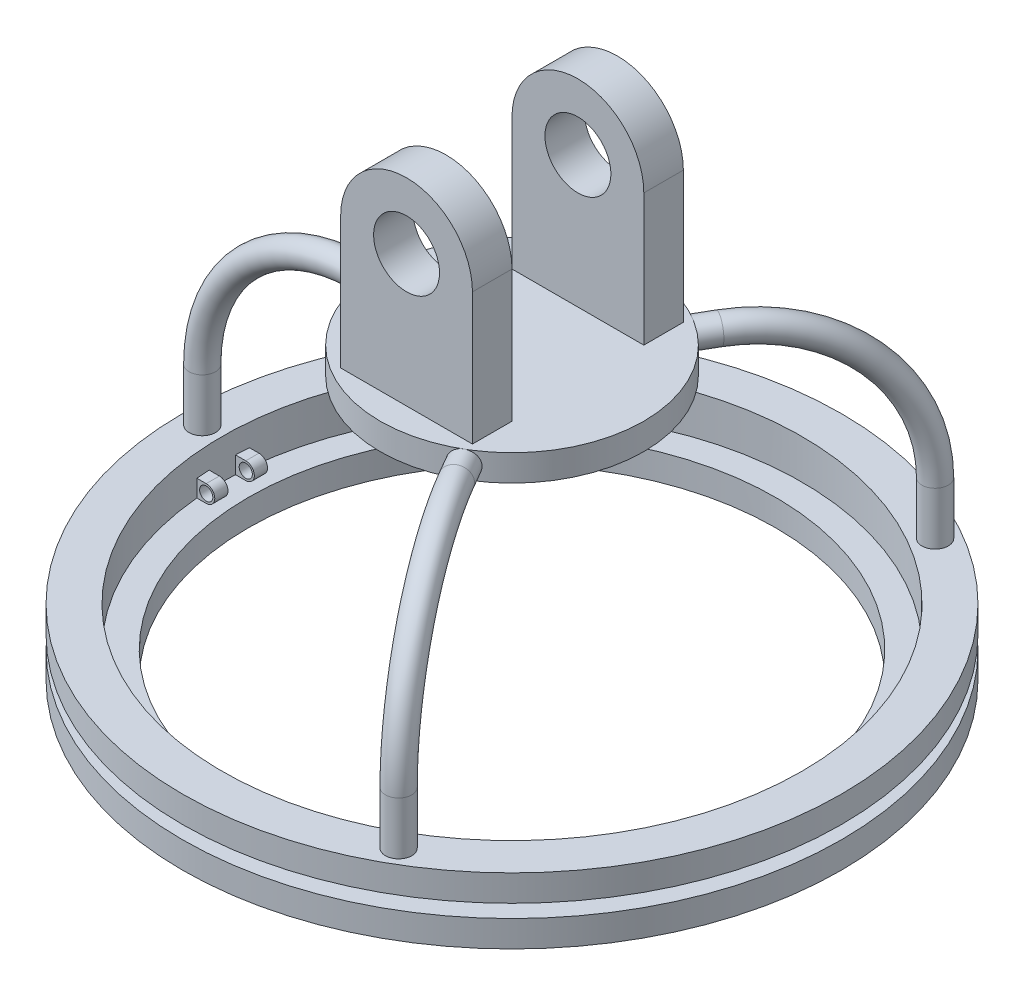
SolidWorks part; units mm, degrees
material "Alumina"
ref_plane "Front Plane" through (0, 0, 0) normal (0, 0, 1) x (1, 0, 0)
ref_plane "Top Plane" through (0, 0, 0) normal (0, 1, 0) x (1, 0, 0)
ref_plane "Right Plane" through (0, 0, 0) normal (1, 0, 0) x (0, 0, -1)
sketch "Sketch1" plane through (0, 0, 0) normal (0, 0, 1) x (1, 0, 0)
  line L0 (0, -571.377) -> (0, 27997.4744) construction
  line L3 (31.75, 6.35) -> (31.75, 3.81)
  line L4 (31.75, 3.81) -> (29.21, 3.81)
  line L5 (29.21, 3.81) -> (29.21, 2.54)
  line L6 (29.21, 2.54) -> (31.75, 2.54)
  line L7 (31.75, 2.54) -> (31.75, 0)
  line L8 (31.75, 0) -> (0, 0)
  line L9 (27.94, 6.35) -> (31.75, 6.35)
  line L10 (27.94, 6.35) -> (27.94, 2.54)
  line L11 (27.94, 2.54) -> (0, 2.54)
  line L12 (0, 2.54) -> (0, 0)
  dimension "D1" = 31.75
  dimension "D3" = 2.54
  dimension "D4" = 2.54
  dimension "D5" = 1.27
  dimension "D6" = 1.27
  dimension "D7" = 2.54
revolve "Revolve1" add sketch "Sketch1" angle 360 about L0
ref_plane "Plane1" through (0, 25.4, 0) normal (0, 1, 0) x (1, 0, 0)
sketch "Sketch2" plane through (0, 2.54, 0) normal (0, 1, 0) x (1, 0, 0)
  circle A0 centre (0, 0) radius 25.4
  dimension "D1" = 50.8
extrude "Cut-Extrude1" cut sketch "Sketch2" against normal up to surface (2.54 mm away) up to face at (31.75, 0, 0)
sketch "Sketch3" plane through (0, 25.4, 0) normal (0, 1, 0) x (1, 0, 0)
  circle A0 centre (0, 0) radius 12.7
  dimension "D1" = 25.4
extrude "Boss-Extrude1" add sketch "Sketch3" along normal blind 2.54 separate body
sketch "Sketch5" plane through (0, 27.94, 0) normal (0, 1, 0) x (1, 0, 0)
  line L0 (-6.35, 10.16) -> (6.35, 10.16)
  line L1 (6.35, 10.16) -> (6.35, 6.35)
  line L2 (6.35, 6.35) -> (-6.35, 6.35)
  line L3 (-6.35, 6.35) -> (-6.35, 10.16)
  line L4 (0, 6.35) -> (0, 0) construction
  dimension "D1" = 6.35
  dimension "D2" = 3.81
  dimension "D3" = 12.7
extrude "Boss-Extrude2" add sketch "Sketch5" along normal blind 12.7
sketch "Sketch6" plane through (0, 0, -6.35) normal (0, 0, 1) x (1, 0, 0)
  line L0 (-6.35, 40.64) -> (6.35, 40.64)
  arc A0 (6.35, 40.64) -> (-6.35, 40.64) centre (0, 40.64) ccw
extrude "Boss-Extrude3" add sketch "Sketch6" against normal up to surface (3.81 mm away) up to face at (0, 34.29, -10.16)
mirror "Mirror1" about plane through (0, 0, 0) normal (0, 0, 1) of "Boss-Extrude3", "Boss-Extrude2"
sketch "Sketch10" plane through (0, 0, -10.16) normal (0, 0, -1) x (-1, 0, 0)
  line L0 (0, 46.99) -> (0, 40.64) construction
  circle A0 centre (0, 40.64) radius 3.175
  arc A1 (6.35, 40.64) -> (-6.35, 40.64) centre (0, 40.64) ccw construction
  dimension "D2" = 6.35
  dimension "D1" = 6.35
extrude "Cut-Extrude2" cut sketch "Sketch10" against normal up to surface (20.32 mm away) up to face at (0, 35.8775, 10.16)
sketch "Sketch11" plane through (0, 0, 0) normal (0, 1, 0) x (1, 0, 0)
  line L0 (-1000, 0) -> (49000, 0) construction
  line L1 (0, 0) -> (-25000, 43301.2702) construction
  line L2 (0, 0) -> (-25000, -43301.2702) construction
  dimension "D1" = 120
  dimension "D2" = 120
ref_plane "Plane3" through (0, 0, 0) normal (0.866, 0, -0.5) x (-0.5, 0, -0.866)
sketch "Sketch12" plane through (0, 0, 0) normal (0.866, 0, -0.5) x (-0.5, 0, -0.866)
  line L0 (-29.845, 6.35) -> (-29.845, 26.67) construction
  line L1 (-29.845, 26.67) -> (-11.9738, 26.67) construction
  line L2 (12.7, 27.94) -> (-12.7, 27.94) construction
  line L3 (-31.75, 6.35) -> (-29.845, 6.35) construction
  line L4 (31.75, 6.35) -> (-31.75, 6.35) construction
  line L5 (-29.845, 6.35) -> (-29.845, 11.43)
  line L6 (-14.605, 26.67) -> (-11.9738, 26.67)
  line L7 (-11.9738, 27.94) -> (-11.9738, 25.4) construction
  line L8 (-11.9738, 40.64) -> (-11.9738, 27.94) construction
  line L9 (34.925, 25.4) -> (-34.925, 25.4) construction
  arc A0 (-29.845, 11.43) -> (-14.605, 26.67) centre (-14.605, 11.43) cw
  point P20 (-11.9738, 26.67)
  dimension "D3" = 15.24
  dimension "D1" = 1.905
  dimension "D2" = 31.75
sweep "Sweep1" add path "Sketch12" circular profile diameter 2.54 parameters "D3"=2.54
pattern_circular "CirPattern2" count 3 over 240 about axis through (0, 0, 0) along (0, 1, 0) of "Sweep1"
sketch "Sketch21" plane through (0, 0, 0) normal (0, 0, 1) x (1, 0, 0)
  line L0 (-28.194, 2.54) -> (-28.194, 4.191)
  line L1 (31.75, 2.54) -> (-31.75, 2.54) construction
  line L2 (-28.194, 4.191) -> (-26.924, 4.191)
  line L3 (27.94, 2.54) -> (-27.94, 2.54) construction
  line L4 (-26.924, 2.54) -> (-28.194, 2.54)
  line L5 (0, 0) -> (0, 12.7) construction
  arc A0 (-26.924, 4.191) -> (-26.924, 2.54) centre (-26.924, 3.3655) cw
  circle A1 centre (-26.924, 3.3655) radius 0.635
  dimension "D2" = 1.27
  dimension "D1" = 1.651
  dimension "D3" = 12.7
  dimension "D4" = 26.924
  dimension "D5" = 1.27
extrude "Boss-Extrude5" add sketch "Sketch21" against normal mid plane 5.08
sketch "Sketch23" plane through (0, 2.54, 0) normal (0, 1, 0) x (1, 0, 0)
  line L0 (-26.0985, -1.27) -> (-27.9111, -1.27)
  line L1 (-26.0985, -2.54) -> (-26.0985, 2.54) construction
  line L2 (-26.0985, -1.27) -> (-26.0985, 1.27)
  line L3 (-26.0985, 1.27) -> (-27.9111, 1.27)
  line L4 (-26.0985, 0) -> (0, 0) construction
  arc A0 (-27.8243, 2.54) -> (-27.8243, -2.54) centre (0, 0) ccw construction
  circle A1 centre (0, 0) radius 27.94 construction
  arc A2 (-27.9111, 1.27) -> (-27.9111, -1.27) centre (0, 0) ccw
  dimension "D1" = 2.54
extrude "Cut-Extrude4" cut sketch "Sketch23" along normal up to surface (1.651 mm away) up to face at (-27.4031, 4.191, 0)
